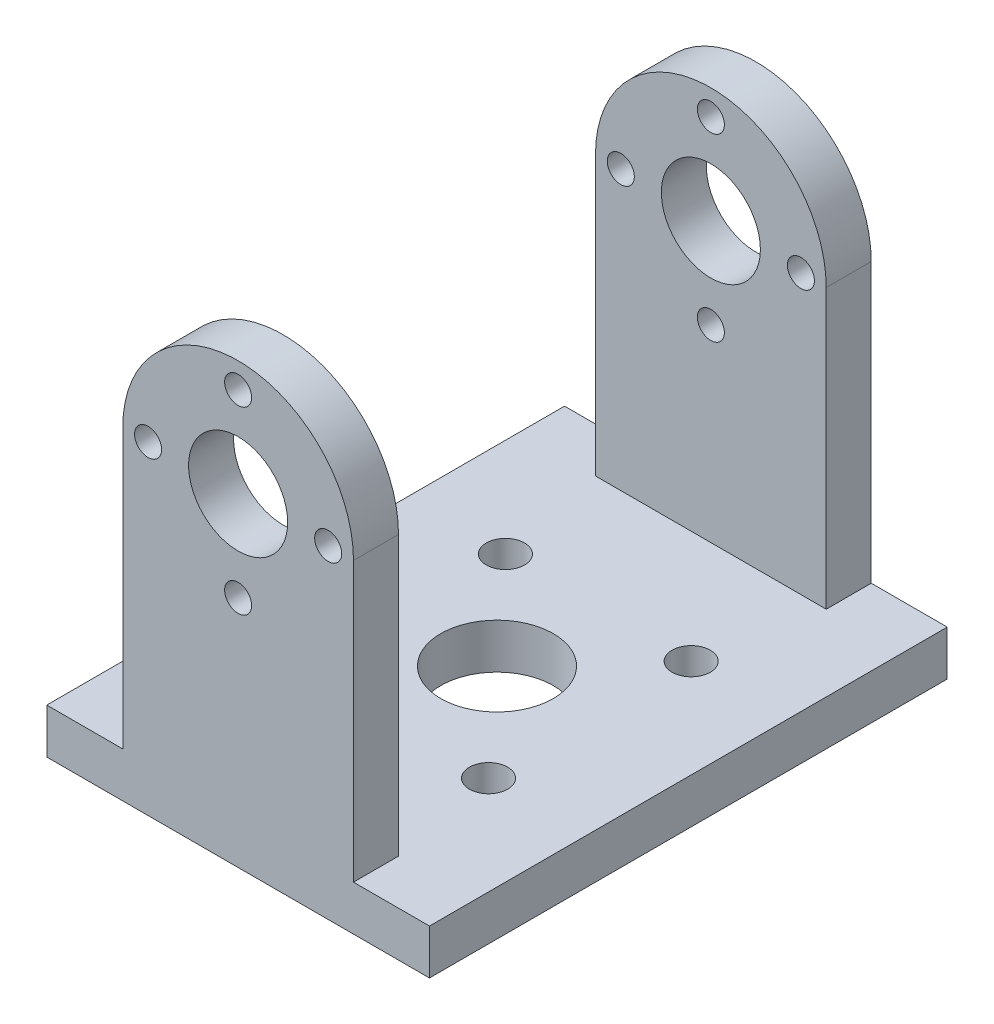
SolidWorks part; units mm, degrees
ref_plane "Front Plane" through (0, 0, 0) normal (0, 0, 1) x (1, 0, 0)
ref_plane "Top Plane" through (0, 0, 0) normal (0, 1, 0) x (1, 0, 0)
ref_plane "Right Plane" through (0, 0, 0) normal (1, 0, 0) x (0, 0, -1)
sketch "Sketch1" plane through (0, 0, 0) normal (0, 0, 1) x (1, 0, 0)
  line L0 (0, 0) -> (0, -68) construction
  line L1 (10.25, 0) -> (10.25, -68)
  line L2 (-10.25, 0) -> (-10.25, -68)
  line L3 (0, 0) -> (0, -68) construction
  line L4 (17, 0) -> (17, -68)
  line L5 (-17, 0) -> (-17, -68)
  line L7 (-10.25, -68) -> (10.25, -68)
  line L8 (-10.25, -68) -> (-10.25, -32.75)
  line L9 (-10.25, -32.75) -> (10.25, -32.75)
  line L10 (10.25, -68) -> (10.25, -32.75)
  line L11 (-17, -32.75) -> (17, -32.75)
  line L12 (-17, -32.75) -> (-17, -28.75)
  line L13 (-17, -28.75) -> (17, -28.75)
  line L14 (17, -32.75) -> (17, -28.75)
  line L15 (-10.25, -68) -> (10.25, -68)
  line L16 (-10.25, -68) -> (-10.25, -79.25)
  line L17 (-10.25, -79.25) -> (10.25, -79.25)
  line L18 (10.25, -68) -> (10.25, -79.25)
  arc A0 (10.25, 0) -> (-10.25, 0) centre (0, 0) ccw
  arc A1 (-10.25, -68) -> (10.25, -68) centre (0, -68) ccw
  arc A2 (17, 0) -> (-17, 0) centre (0, 0) ccw
  arc A3 (-17, -68) -> (17, -68) centre (0, -68) ccw
  circle A4 centre (0, 0) radius 8
  circle A5 centre (0, 8) radius 1.2
  circle A6 centre (8, 0) radius 1.2
  circle A7 centre (0, -8) radius 1.2
  circle A8 centre (-8, 0) radius 1.2
  circle A9 centre (0, -68) radius 10.25
  circle A10 centre (0, 0) radius 4.4
  point P3 (0, -34)
  point P10 (0, -34)
  point P28 (0, 0)
  dimension "D2" = 10.25
  dimension "D3" = 17
  dimension "D4" = 16
  dimension "D5" = 2.4
  dimension "D10" = 8.8
  dimension "D1" = 68
  dimension "D7" = 35.25
  dimension "D8" = 4
  dimension "D9" = 11.25
  dimension "D6" = 4
extrude "Boss-Extrude1" add sketch "Sketch1" along normal blind 4 contours A8 A4 A7 A6 A5 A10 | L1 A0 L2 L13 A8 A4 A5 A6 A7
sketch "Sketch3" plane through (0, -28.75, 0) normal (0, -1, 0) x (-1, 0, 0)
  line L21 (-10.25, -4) -> (-10.25, 0) construction
  line L22 (-17, 0) -> (17, 0)
  line L23 (-17, 0) -> (-17, -46)
  line L24 (-17, -46) -> (17, -46)
  line L25 (17, 0) -> (17, -46)
  line L28 (10.25, 0) -> (-10.25, 0) construction
  circle A0 centre (0, -23) radius 5
  circle A1 centre (-8.25, -14) radius 1.7
  circle A2 centre (8.25, -14) radius 1.7
  circle A3 centre (8.25, -32) radius 1.7
  circle A4 centre (-8.25, -32) radius 1.7
  dimension "D3" = 3.4
  dimension "D4" = 9
  dimension "D5" = 8.25
  dimension "D8" = 23
  dimension "D10" = 8.25
  dimension "D11" = 9
  dimension "D13" = 17
  dimension "D1" = 34
  dimension "D2" = 6.75
  dimension "D9" = 46
  dimension "D12" = 0
  dimension "D6" = 2
  dimension "D7" = 2
extrude "Boss-Extrude3" add sketch "Sketch3" against normal blind 4
ref_plane "Plane1" through (0, 0, 23) normal (0, 0, 1) x (1, 0, 0)
mirror "Mirror1" about plane through (0, 0, 23) normal (0, 0, 1) of "Boss-Extrude1"
